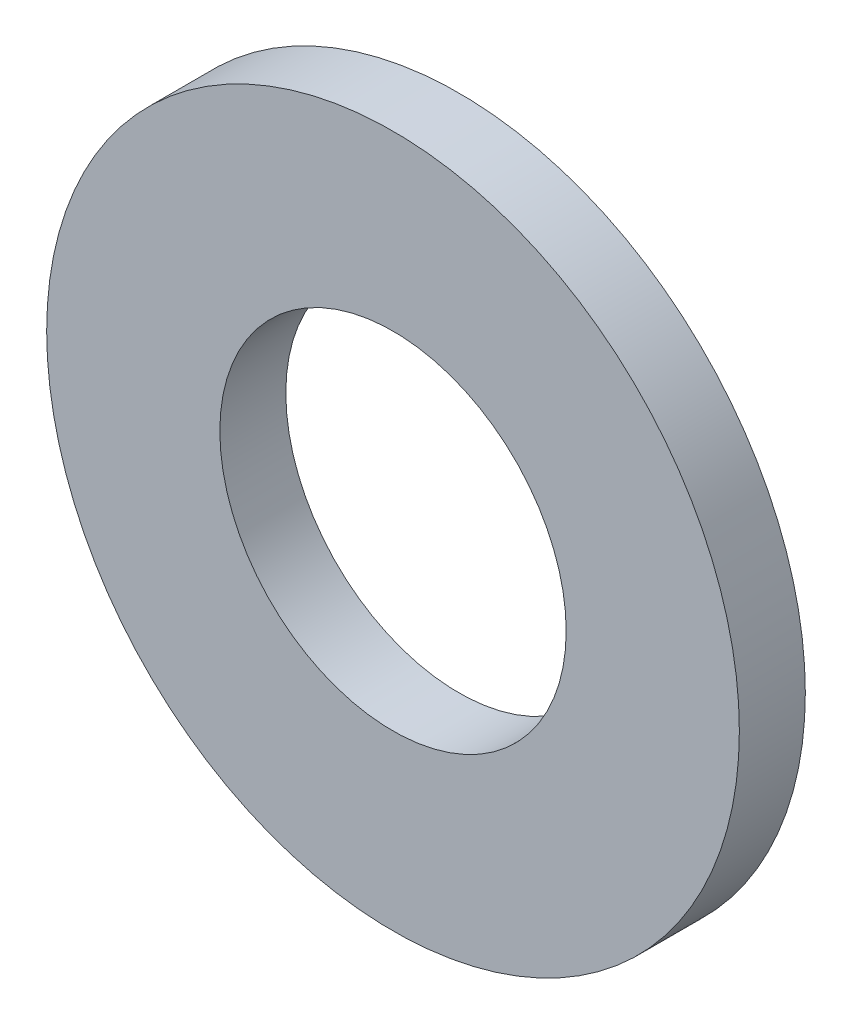
SolidWorks part; units mm, degrees
ref_plane "Спереди" through (0, 0, 0) normal (0, 0, 1) x (1, 0, 0)
ref_plane "Сверху" through (0, 0, 0) normal (0, 1, 0) x (1, 0, 0)
ref_plane "Справа" through (0, 0, 0) normal (1, 0, 0) x (0, 0, -1)
sketch "Эскиз1" plane through (0, 0, 0) normal (0, 0, 1) x (1, 0, 0)
  circle A0 centre (0, 0) radius 5.25
  circle A1 centre (0, 0) radius 10.5
  dimension "D1" = 21
  dimension "D2" = 10.5
extrude "Вытянуть1" add sketch "Эскиз1" along normal blind 2
